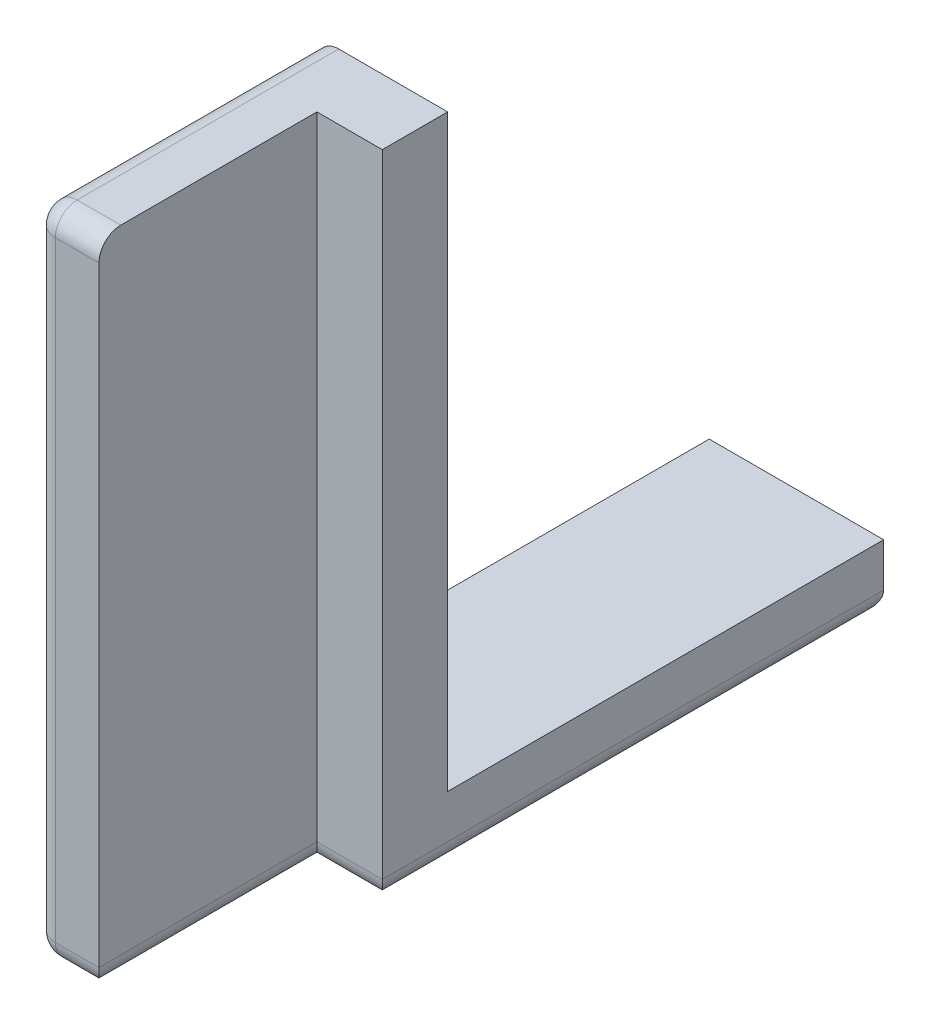
SolidWorks part; units mm, degrees
ref_plane "Front Plane" through (0, 0, 0) normal (0, 0, 1) x (1, 0, 0)
ref_plane "Top Plane" through (0, 0, 0) normal (0, 1, 0) x (1, 0, 0)
ref_plane "Right Plane" through (0, 0, 0) normal (1, 0, 0) x (0, 0, -1)
sketch "Sketch1" plane through (0, 0, 0) normal (0, 0, 1) x (1, 0, 0)
  line L0 (0, -30) -> (0, 0)
  line L3 (0, -30) -> (3, -30)
  line L4 (3, -30) -> (3, 0)
  line L5 (3, 0) -> (0, 0)
  dimension "D1" = 3
  dimension "D2" = 30
extrude "Boss-Extrude1" add sketch "Sketch1" along normal blind 3
sketch "Sketch8" plane through (0, 0, 0) normal (0, 0, -1) x (-1, 0, 0)
  line L0 (-3, -30) -> (0, -30)
  line L1 (0, -30) -> (0, -27)
  line L2 (0, 0) -> (0, -30) construction
  line L3 (0, -27) -> (-3, -27)
  line L4 (-3, -30) -> (-3, 0) construction
  line L5 (-3, -27) -> (-3, -30)
  dimension "D1" = 3
extrude "Boss-Extrude7" add sketch "Sketch8" along normal blind 20
sketch "Sketch9" plane through (0, 0, 0) normal (-1, 0, 0) x (0, 0, 1)
  line L0 (-20, -27) -> (0, -27)
  line L1 (0, -27) -> (0, -30)
  line L2 (3, -30) -> (-20, -30) construction
  line L3 (0, -30) -> (-20, -30)
  line L4 (-20, -30) -> (-20, -27)
extrude "Boss-Extrude8" add sketch "Sketch9" along normal blind 5
sketch "Sketch12" plane through (0, 0, 0) normal (-1, 0, 0) x (0, 0, 1)
  line L0 (0, 0) -> (0, -30)
  line L1 (0, -30) -> (3, -30)
  line L2 (3, -30) -> (3, 0)
  line L3 (3, 0) -> (0, 0)
extrude "Boss-Extrude10" add sketch "Sketch12" along normal blind 3
sketch "Sketch13" plane through (0, 0, 3) normal (0, 0, 1) x (1, 0, 0)
  line L0 (-3, 0) -> (-3, -30)
  line L1 (-3, -30) -> (0, -30)
  line L2 (-3, -30) -> (3, -30) construction
  line L3 (0, -30) -> (0, 0)
  line L4 (3, 0) -> (-3, 0) construction
  line L5 (0, 0) -> (-3, 0)
  dimension "D1" = 3
extrude "Boss-Extrude11" add sketch "Sketch13" along normal blind 10
fillet "Fillet6" radius 1 12 edges at (3, -30, -8.5) (-1, -30, -20) (-5, -30, -10) (-4, -30, 0) (-3, -30, 6.5) (-1.5, -30, 13) (0, -30, 8) (1.5, -30, 3) (-5, -28.5, 0) (-3, -15, 13) (-3, 0, 6.5) (-1.5, 0, 13)
